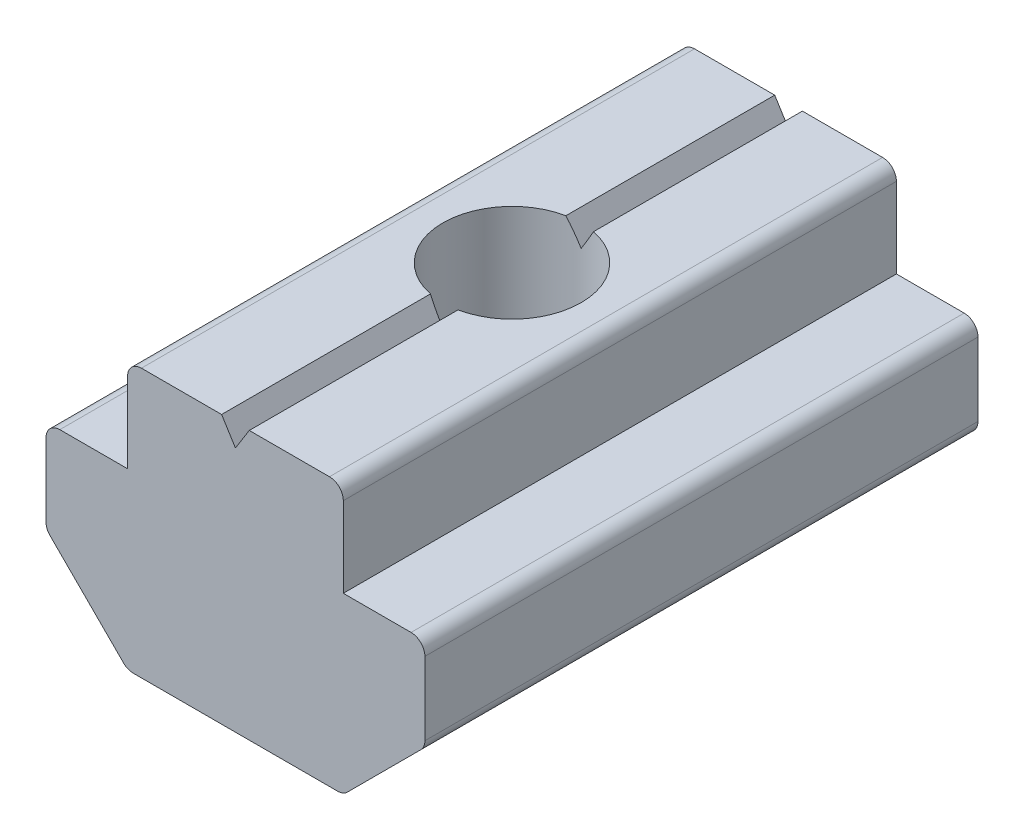
SolidWorks part; units mm, degrees
ref_plane "前视基准面" through (0, 0, 0) normal (0, 0, 1) x (1, 0, 0)
ref_plane "上视基准面" through (0, 0, 0) normal (0, 1, 0) x (1, 0, 0)
ref_plane "右视基准面" through (0, 0, 0) normal (1, 0, 0) x (0, 0, -1)
sketch "草图1" plane through (0, 0, 0) normal (0, 0, 1) x (1, 0, 0)
  line B0 (-0.1622, 0.1464) -> (-2.8193, 2.8036)
  line B1 (-2.9658, 3.1571) -> (-2.9658, 5.8)
  line B2 (-2.4658, 6.3) -> (-0.0158, 6.3)
  line B3 (-0.0158, 6.3) -> (-0.0158, 9.2)
  line B4 (0.4842, 9.7) -> (3.3842, 9.7)
  line B5 (4.3842, 9.7) -> (7.2842, 9.7)
  line B6 (7.7842, 9.2) -> (7.7842, 6.3)
  line B7 (7.7842, 6.3) -> (10.2342, 6.3)
  line B8 (10.7342, 5.8) -> (10.7342, 3.1571)
  line B9 (10.5878, 2.8036) -> (7.9307, 0.1464)
  line B10 (7.5771, 0) -> (0.1913, 0)
  line B11 (3.8842, 8.9) -> (3.3842, 9.7)
  line B12 (3.8842, 8.9) -> (4.3842, 9.7)
  arc B13 (-2.9658, 3.1571) -> (-2.8193, 2.8036) centre (-2.4658, 3.1571) ccw
  arc B14 (-2.4658, 6.3) -> (-2.9658, 5.8) centre (-2.4658, 5.8) ccw
  arc B15 (0.4842, 9.7) -> (-0.0158, 9.2) centre (0.4842, 9.2) ccw
  arc B16 (7.7842, 9.2) -> (7.2842, 9.7) centre (7.2842, 9.2) ccw
  arc B17 (10.7342, 5.8) -> (10.2342, 6.3) centre (10.2342, 5.8) ccw
  arc B18 (10.5878, 2.8036) -> (10.7342, 3.1571) centre (10.2342, 3.1571) ccw
  arc B19 (7.5771, 0) -> (7.9307, 0.1464) centre (7.5771, 0.5) ccw
  arc B20 (-0.1622, 0.1464) -> (0.1913, 0) centre (0.1913, 0.5) ccw
sketch_block_instance "A$C42F501EE-1"
sketch_block "A$C42F501EE"
extrude "凸台-拉伸1" add sketch "草图1" along normal mid plane 20
sketch "草图3" plane through (0, 0, 0) normal (0, -1, 0) x (1, 0, 0)
  line L0 (0.1913, 10) -> (7.5771, 10) construction
  point P0 (3.8842, 0)
  dimension "D1" = 10
hole_wizard "M6 螺纹孔1" positions "3D草图1" profile "草图4" tap size "M6" standard "Iso"
sketch3d "3D草图1"
  point P0 (3.8842, 0, 0)
sketch "草图4" plane through (3.8842, 0, 0) normal (1, 0, 0) x (0, 0, -1)
  line L0 (0, 0) -> (0, 16.5022)
  line L1 (0, 16.5022) -> (2.5, 15)
  line L2 (2.5, 15) -> (2.5, 0)
  line L5 (2.5, 0) -> (0, 0)
  line L10 (0, 16.5022) -> (-2.5, 15) construction
  line L11 (0, -6.35) -> (0, 107.95) construction
  dimension "螺纹孔钻头直径" = 5
  dimension "螺纹孔钻头深度" = 15
  dimension "导头角度" = 118
cosmetic thread "孔螺蚊线1" parameters "D1"=9.7, "D2"=6
